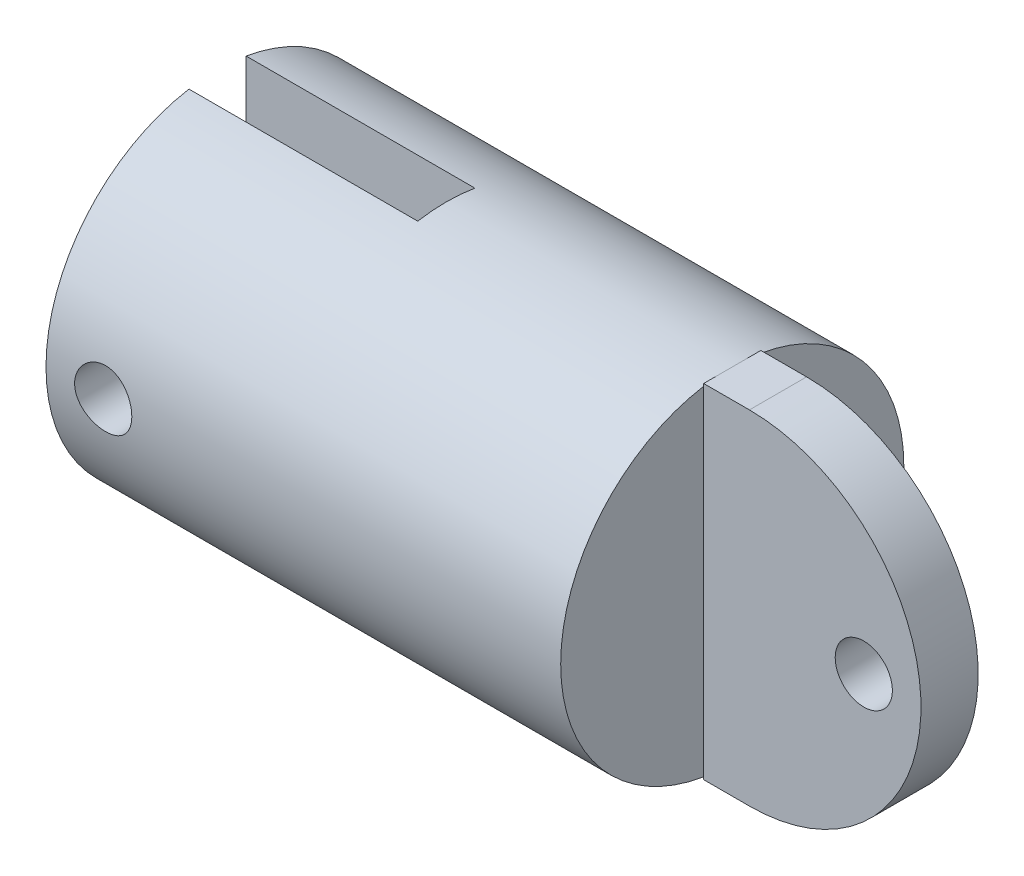
SolidWorks part; units mm, degrees
ref_plane "Front Plane" through (0, 0, 0) normal (0, 0, 1) x (1, 0, 0)
ref_plane "Top Plane" through (0, 0, 0) normal (0, 1, 0) x (1, 0, 0)
ref_plane "Right Plane" through (0, 0, 0) normal (1, 0, 0) x (0, 0, -1)
sketch "Sketch2" plane through (0, 0, 0) normal (1, 0, 0) x (0, 0, -1)
  circle A0 centre (0, 0) radius 15
  dimension "D1" = 30
extrude "Boss-Extrude1" add sketch "Sketch2" against normal blind 45
sketch "Sketch3" plane through (0, 0, 0) normal (0, 1, 0) x (1, 0, 0)
  line L0 (-45, 15) -> (-45, -15) construction
  line L1 (-45, 2.5) -> (-25, 2.5)
  line L2 (-45, 2.5) -> (-45, -2.5)
  line L3 (-45, -2.5) -> (-25, -2.5)
  line L4 (-25, 2.5) -> (-25, -2.5)
  line L5 (0, 15) -> (-45, 15) construction
  dimension "D1" = 5
  dimension "D2" = 20
  dimension "D3" = 0
  dimension "D4" = 12.5
extrude "Cut-Extrude1" cut sketch "Sketch3" against normal through all and the other way through all
sketch "Sketch6" plane through (0, 0, 0) normal (0, 0, 1) x (1, 0, 0)
  line L0 (-45, 14.7902) -> (-45, -14.7902) construction
  circle A0 centre (-40, 0) radius 2.5
  dimension "D2" = 5
  dimension "D1" = 5
  dimension "D3" = 0
extrude "Cut-Extrude2" cut sketch "Sketch6" against normal through all and the other way through all
sketch "Sketch7" plane through (0, 0, 0) normal (1, 0, 0) x (0, 0, -1)
  line L0 (-2.5, 15) -> (-2.5, -15)
  line L1 (-2.5, 15) -> (2.5, 15)
  line L2 (-2.5, -15) -> (2.5, -15)
  line L3 (2.5, 15) -> (2.5, -15)
  line L4 (-2.5, 15) -> (2.5, -15) construction
  line L5 (-2.5, -15) -> (2.5, 15) construction
  point P1 (0, 0)
  dimension "D1" = 5
extrude "Boss-Extrude2" add sketch "Sketch7" along normal blind 4
sketch "Sketch8" plane through (0, 0, 2.5) normal (0, 0, 1) x (1, 0, 0)
  line L0 (4, 15) -> (4, -15) construction
  line L1 (4, 15) -> (4, -15)
  arc A0 (4, -15) -> (4, 15) centre (4, 0) ccw
extrude "Boss-Extrude3" add sketch "Sketch8" against normal blind 5
sketch "Sketch9" plane through (0, 0, 2.5) normal (0, 0, 1) x (1, 0, 0)
  circle A0 centre (14, 0) radius 2.5
  arc A1 (4, -15) -> (4, 15) centre (4, 0) ccw construction
  point P5 (19, 0)
  dimension "D1" = 5
  dimension "D2" = 5
extrude "Cut-Extrude3" cut sketch "Sketch9" against normal through all and the other way through all
